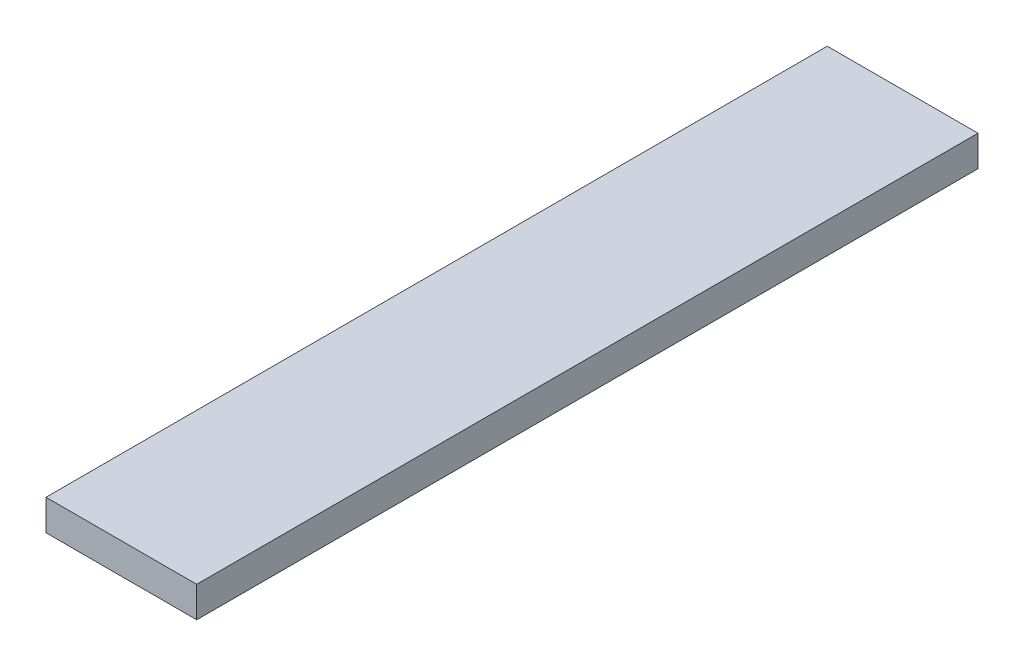
SolidWorks part; units mm, degrees
ref_plane "前视基准面" through (0, 0, 0) normal (0, 0, 1) x (1, 0, 0)
ref_plane "上视基准面" through (0, 0, 0) normal (0, 1, 0) x (1, 0, 0)
ref_plane "右视基准面" through (0, 0, 0) normal (1, 0, 0) x (0, 0, -1)
other "Configuration Table"
sketch "草图1" plane through (0, 0, 0) normal (0, 1, 0) x (1, 0, 0)
  line L1 (-4.9, 25.4) -> (4.9, 25.4)
  line L2 (-4.9, 25.4) -> (-4.9, -25.4)
  line L3 (-4.9, -25.4) -> (4.9, -25.4)
  line L4 (4.9, 25.4) -> (4.9, -25.4)
  line L5 (-4.9, 25.4) -> (4.9, -25.4) construction
  line L6 (-4.9, -25.4) -> (4.9, 25.4) construction
  point P0 (0, 0)
  dimension "D1" = 50.8
  dimension "D2" = 9.8
extrude "凸台-拉伸1" add sketch "草图1" along normal blind 2
